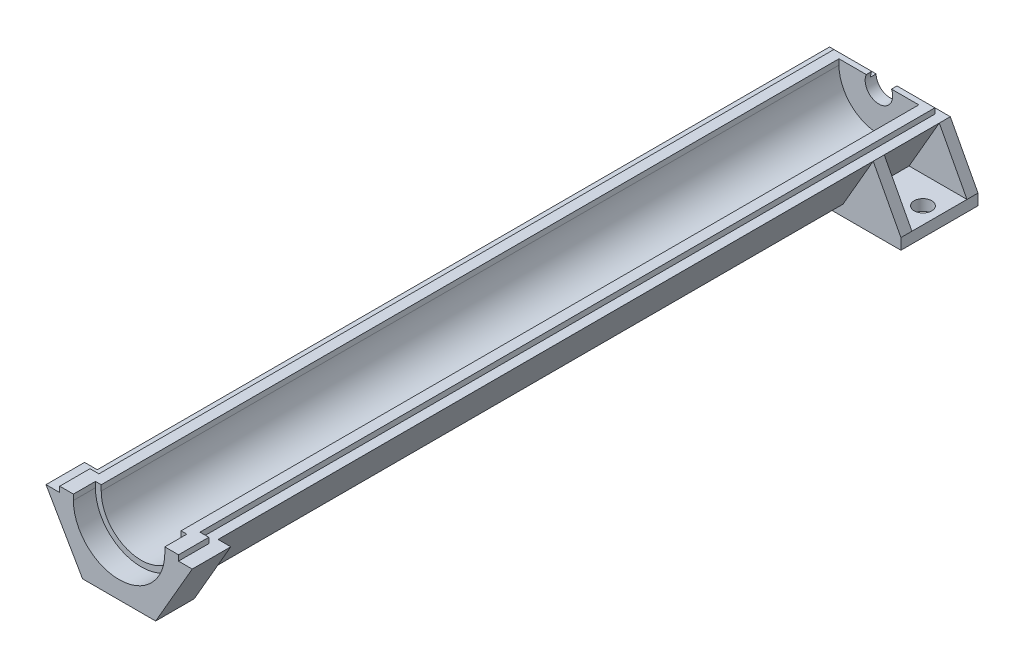
SolidWorks part; units mm, degrees
material "ABS"
ref_plane "Ebene vorne" through (0, 0, 0) normal (0, 0, 1) x (1, 0, 0)
ref_plane "Ebene oben" through (0, 0, 0) normal (0, 1, 0) x (1, 0, 0)
ref_plane "Ebene rechts" through (0, 0, 0) normal (1, 0, 0) x (0, 0, -1)
sketch "Skizze1" plane through (0, 0, 0) normal (0, 0, 1) x (1, 0, 0)
  line L0 (7.25, 0) -> (10.9697, 0)
  line L1 (-7.25, 0) -> (-10.9697, 0)
  line L3 (-10.9697, 0) -> (-5.4848, -9.5)
  line L4 (-5.4848, -9.5) -> (5.4848, -9.5)
  line L5 (5.4848, -9.5) -> (10.9697, 0)
  arc A0 (-7.25, 0) -> (7.25, 0) centre (0, 0) ccw
  point P3 (0, 0)
  dimension "D1" = 21.9393
  dimension "D2" = 60
  dimension "D4" = 9.5
extrude "Aufsatz-Linear austragen1" add sketch "Skizze1" along normal blind 136
sketch "Skizze2" plane through (0, 0, 0) normal (0, 0, 1) x (1, 0, 0)
  line L0 (7.25, 0) -> (-7.25, 0)
  arc A0 (-7.25, 0) -> (7.25, 0) centre (0, 0) ccw
  arc A1 (-7.25, 0) -> (7.25, 0) centre (0, 0) ccw construction
extrude "Aufsatz-Linear austragen2" add sketch "Skizze2" along normal blind 2
sketch3d "3D-Skizze5" plane through (0, 0, 0) normal (0, 0, 1) x (1, 0, 0)
  dimension "D1" = 133
sketch "Skizze3" plane through (0, 0, 133) normal (0, 0, 1) x (1, 0, 0)
  line L3 (-8.3, 0) -> (-13.2791, 0)
  line L4 (8.3, 0) -> (13.2791, 0)
  line L5 (-5.4848, -9.5) -> (5.4848, -9.5) construction
  line L6 (-7.25, 0) -> (-10.9697, 0) construction
  line L10 (-13.2791, 0) -> (-6.6395, -11.5)
  line L11 (-6.6395, -11.5) -> (6.6395, -11.5)
  line L12 (6.6395, -11.5) -> (13.2791, 0)
  line L16 (19.2833, -10.3997) -> (11.5579, 2.9811) [skipped]
  line L17 (15.576, 11.5) -> (0.1251, 11.5) [skipped]
  line L18 (-3.3785, 17.1483) -> (-11.1039, 3.7674) [skipped]
  arc A0 (8.3, 0) -> (-8.3, 0) centre (0, 0) cw
  dimension "D1" = 16.6
  dimension "D2" = 2
extrude "Aufsatz-Linear austragen3" add sketch "Skizze3" along normal blind 7
sketch "Skizze7" plane through (0, 0, 0) normal (0, 0, 1) x (1, 0, 0)
  line L0 (10.9697, 0) -> (5.4848, -9.5)
  line L1 (5.4848, -9.5) -> (16, -9.5)
  line L2 (16, -9.5) -> (10.9697, 0)
  line L3 (-5.4848, -9.5) -> (-10.9697, 0)
  line L4 (-10.9697, 0) -> (-16, -9.5)
  line L5 (-16, -9.5) -> (-5.4848, -9.5)
  dimension "D1" = 32
extrude "Aufsatz-Linear austragen6" add sketch "Skizze7" along normal blind 2
pattern_linear "Lineares Muster3" count 2 spacing 12 along (0, 0, 1) of "Aufsatz-Linear austragen6"
sketch "Skizze12" plane through (0, -9.5, 0) normal (0, -1, 0) x (1, 0, 0)
  line L1 (-16, 14) -> (16, 14)
  line L2 (-16, 14) -> (-16, 0)
  line L3 (-16, 0) -> (16, 0)
  line L4 (16, 14) -> (16, 0)
  circle A0 centre (-13, 7) radius 1.6
  circle A1 centre (13, 7) radius 1.6
  dimension "D1" = 3.2
  dimension "D7" = 7
  dimension "D2" = 14
  dimension "D3" = 32
  dimension "D4" = 3
  dimension "D5" = 3
  dimension "D8" = 7
  dimension "D6" = 2
extrude "Aufsatz-Linear austragen14" add sketch "Skizze12" along normal blind 2
sketch "Skizze13" plane through (0, 0, 0) normal (0, 1, 0) x (1, 0, 0)
  line L0 (8.3, -140) -> (10.7895, -140)
  line L1 (13.2791, -140) -> (8.3, -140) construction
  line L2 (10.7895, -140) -> (10.7895, -134.5)
  line L3 (10.7895, -134.5) -> (9.1697, -134.5)
  line L4 (9.1697, -134.5) -> (9.1697, -1)
  line L5 (9.1697, -1) -> (-9.1697, -1)
  line L6 (-9.1697, -1) -> (-9.1697, -134.5)
  line L7 (-8.3, -140) -> (-10.7895, -140)
  line L8 (-8.3, -140) -> (-13.2791, -140) construction
  line L9 (-10.7895, -140) -> (-10.7895, -134.5)
  line L10 (-10.7895, -134.5) -> (-9.1697, -134.5)
  line L11 (-8.3, -140) -> (-8.3, -136)
  line L12 (-8.3, -136) -> (-7.25, -136)
  line L13 (-7.25, -136) -> (-7.25, -2)
  line L14 (-7.25, -2) -> (7.25, -2)
  line L15 (7.25, -2) -> (7.25, -136)
  line L16 (7.25, -136) -> (8.3, -136)
  line L17 (8.3, -136) -> (8.3, -140)
  line L18 (10.9697, -133) -> (10.9697, -14) construction
  line L19 (-10.9697, -133) -> (-10.9697, -14) construction
  line L20 (-5.7475, -133) -> (5.7475, -133) construction
  line L21 (13.2791, -133) -> (10.9697, -133) construction
  line L22 (10.9697, 0) -> (-10.9697, 0) construction
  dimension "D1" = 3.7197
  dimension "D2" = 1.8
  dimension "D3" = 1.8
  dimension "D4" = 1.5
  dimension "D5" = 1.5
  dimension "D6" = 1
extrude "Aufsatz-Linear austragen15" add sketch "Skizze13" along normal blind 1
sketch "Skizze14" plane through (0, 0, 0) normal (0, 0, -1) x (-1, 0, 0)
  circle A0 centre (0, 0) radius 2.5
  dimension "D1" = 5
extrude "Schnitt-Linear austragen1" cut sketch "Skizze14" against normal up to surface (2 mm away)
